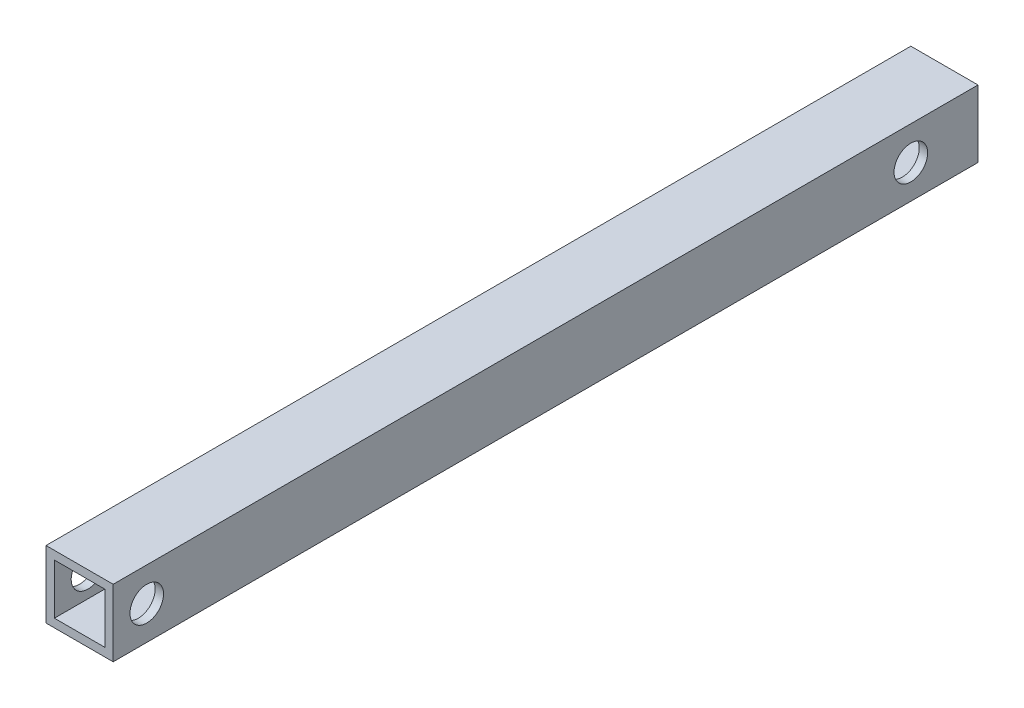
SolidWorks part; units mm, degrees
ref_plane "Front Plane" through (0, 0, 0) normal (0, 0, 1) x (1, 0, 0)
ref_plane "Top Plane" through (0, 0, 0) normal (0, 1, 0) x (1, 0, 0)
ref_plane "Right Plane" through (0, 0, 0) normal (1, 0, 0) x (0, 0, -1)
sketch "Sketch1" plane through (0, 0, 0) normal (0, 0, 1) x (1, 0, 0)
  line L7 (0, 0) -> (-25.4, 0)
  line L8 (0, 0) -> (0, 25.4)
  line L9 (0, 25.4) -> (-25.4, 25.4)
  line L10 (-25.4, 0) -> (-25.4, 25.4)
  line L11 (-3.175, 22.225) -> (-22.225, 22.225)
  line L12 (-3.175, 22.225) -> (-3.175, 3.175)
  line L13 (-3.175, 3.175) -> (-22.225, 3.175)
  line L14 (-22.225, 22.225) -> (-22.225, 3.175)
  dimension "D1" = 25.4
  dimension "D2" = 25.4
  dimension "D3" = 3.175
  dimension "D4" = 3.175
  dimension "D5" = 3.175
  dimension "D6" = 3.175
extrude "Boss-Extrude1" add sketch "Sketch1" along normal blind 327.025
sketch "Sketch5" plane through (0, 0, 0) normal (1, 0, 0) x (0, 0, -1)
  line L0 (0, 0) -> (0, 25.4) construction
  line L1 (-327.025, 0) -> (-327.025, 25.4) construction
  circle A0 centre (-25.4, 12.7) radius 6.35
  circle A1 centre (-314.325, 12.7) radius 6.35
  dimension "D1" = 25.4
  dimension "D2" = 12.7
extrude "Cut-Extrude4" cut sketch "Sketch5" against normal through all
